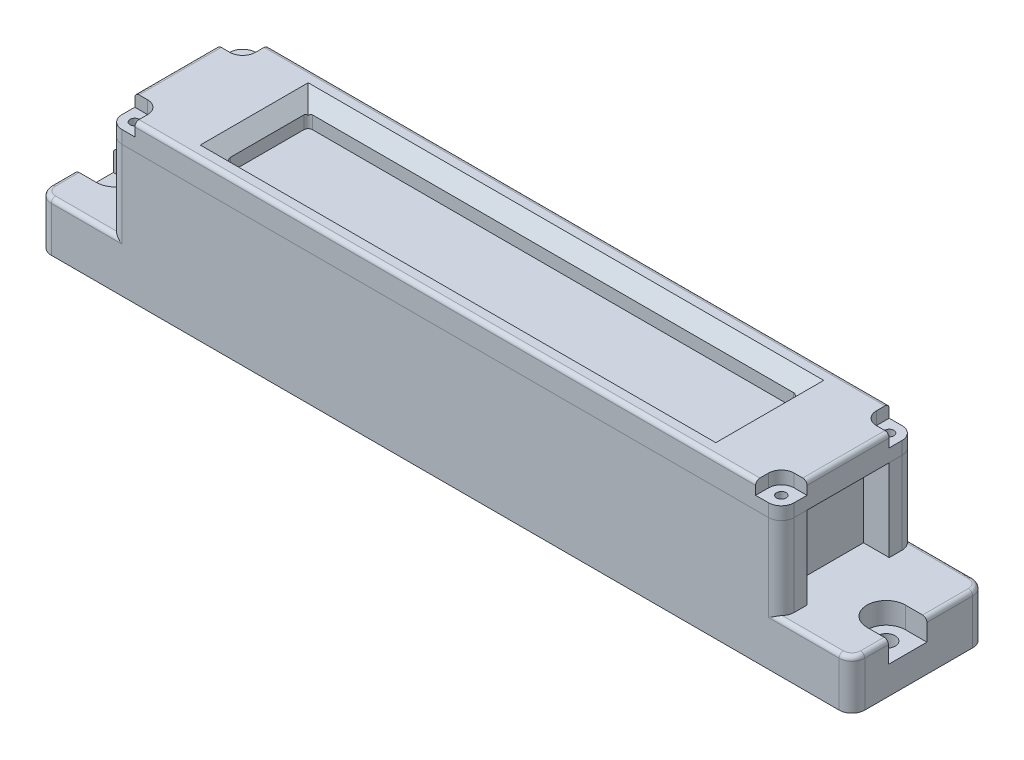
SolidWorks part; units mm, degrees
ref_plane "正面" through (0, 0, 0) normal (0, 0, 1) x (1, 0, 0)
ref_plane "平面" through (0, 0, 0) normal (0, 1, 0) x (1, 0, 0)
ref_plane "右側面" through (0, 0, 0) normal (1, 0, 0) x (0, 0, -1)
sketch "ｽｹｯﾁ1" plane through (0, 0, 0) normal (0, 1, 0) x (1, 0, 0)
  line L1 (-72.2, 11.6) -> (72.2, 11.6)
  line L2 (-72.2, 11.6) -> (-72.2, -11.6)
  line L3 (-72.2, -11.6) -> (72.2, -11.6)
  line L4 (72.2, 11.6) -> (72.2, -11.6)
  point P4 (-72.2, 0)
  point P6 (0, 11.6)
  dimension "D1" = 144.4
  dimension "D2" = 23.2
extrude "本体" add sketch "ｽｹｯﾁ1" along normal mid plane 23.2
sketch "ｽｹｯﾁ2" plane through (0, -11.6, 0) normal (0, -1, 0) x (1, 0, 0)
  line L0 (72.2, -11.6) -> (-72.2, -11.6) construction
  line L1 (-95, -15.6) -> (95, -15.6)
  line L2 (-95, -15.6) -> (-95, 15.6)
  line L3 (-95, 15.6) -> (95, 15.6)
  line L4 (95, -15.6) -> (95, 15.6)
  line L5 (-72.2, 0) -> (72.2, 0) construction
  line L6 (-72.2, -11.6) -> (-72.2, 11.6) construction
  line L7 (72.2, 11.6) -> (72.2, -11.6) construction
  line L8 (-85, -15.6) -> (-85, 15.6) construction
  line L9 (0, -15.6) -> (0, 15.6) construction
  line L18 (-72.6, 12) -> (-72.6, -12)
  line L19 (72.6, 12) -> (-72.6, 12)
  line L20 (72.6, -12) -> (72.6, 12)
  line L21 (-72.6, -12) -> (72.6, -12)
  line L22 (-72.6, 12) -> (-72.6, -12) construction
  line L23 (72.6, 12) -> (-72.6, 12) construction
  line L24 (72.6, -12) -> (72.6, 12) construction
  line L25 (-72.6, -12) -> (72.6, -12) construction
  circle A0 centre (-90, 2.6) radius 5 construction
  circle A1 centre (-90, 2.6) radius 2.1
  circle A2 centre (90, 2.6) radius 2.1
  point P12 (-95, 0)
  dimension "D3" = 10
  dimension "D4" = 4.2
  dimension "D1" = 4
  dimension "D2" = 12.8
  dimension "D6" = 13
  dimension "D7" = 180
  dimension "D5" = 0.4
extrude "ﾎﾞｽ - 押し出し2" add sketch "ｽｹｯﾁ2" along normal blind 6.5 separate body
sketch "ｽｹｯﾁ3" plane through (0, -11.6, 0) normal (0, 1, 0) x (1, 0, 0)
  line L0 (-95, -15.6) -> (-95, 15.6) construction
  line L1 (-90, 1.9) -> (-95, 1.9)
  line L3 (-90, -7.1) -> (-95, -7.1)
  line L4 (-95, 15.6) -> (-95, -15.6)
  line L5 (-95, -15.6) -> (95, -15.6)
  line L6 (95, -15.6) -> (95, 15.6)
  line L7 (95, 15.6) -> (-95, 15.6)
  line L8 (-95, 15.6) -> (-95, -15.6)
  line L9 (-95, -15.6) -> (95, -15.6)
  line L10 (95, -15.6) -> (95, 15.6)
  line L11 (95, 15.6) -> (-95, 15.6)
  line L19 (0, 15.6) -> (0, -15.6) construction
  line L20 (90, -7.1) -> (95, -7.1)
  line L21 (90, 1.9) -> (95, 1.9)
  line L23 (-72.5, 11.9) -> (-72.5, -11.9)
  line L24 (-72.5, -11.9) -> (72.5, -11.9)
  line L25 (72.5, -11.9) -> (72.5, 11.9)
  line L26 (72.5, 11.9) -> (-72.5, 11.9)
  line L27 (-72.5, 11.9) -> (-72.5, -11.9)
  line L28 (-72.5, -11.9) -> (72.5, -11.9)
  line L29 (72.5, -11.9) -> (72.5, 11.9)
  line L30 (72.5, 11.9) -> (-72.5, 11.9)
  arc A0 (-90, -7.1) -> (-90, 1.9) centre (-90, -2.6) ccw
  arc A1 (90, -7.1) -> (90, 1.9) centre (90, -2.6) cw
  line M12 (-95, 15.6) -> (-95, -15.6)
  line M13 (-95, -15.6) -> (95, -15.6)
  line M14 (95, -15.6) -> (95, 15.6)
  line M15 (95, 15.6) -> (-95, 15.6)
  dimension "D2" = 4.5
  dimension "D1" = 0
  dimension "D3" = 0.3
extrude "ﾎﾞｽ - 押し出し3" add sketch "ｽｹｯﾁ3" along normal blind 5 contours L19 L11 L1 A0 L3 L28 L27 L30 M12 M13 | L19 L30 L29 L28 L9 L20 A1 L21 M15 M14
sketch "ｽｹｯﾁ4" plane through (0, -6.6, 0) normal (0, 1, 0) x (1, 0, 0)
  line L0 (72.5, -11.9) -> (72.5, 11.9) construction
  line L1 (-72.5, -11.9) -> (72.5, -11.9) construction
  line L2 (72.5, 11.9) -> (-72.5, 11.9) construction
  line L3 (-72.5, 11.9) -> (-72.5, -11.9) construction
  line L4 (72.5, -11.9) -> (72.5, 11.9)
  line L5 (-72.5, -11.9) -> (72.5, -11.9)
  line L6 (72.5, 11.9) -> (-72.5, 11.9)
  line L7 (-72.5, 11.9) -> (-72.5, 9.6)
  line L8 (78.5, 15.6) -> (-78.5, 15.6)
  line L9 (-78.5, 15.6) -> (-78.5, 9.6)
  line L10 (-78.5, -15.6) -> (78.5, -15.6)
  line L11 (-78.5, -9.6) -> (-72.5, -9.6)
  line L12 (95, 15.6) -> (-95, 15.6) construction
  line L13 (-95, -15.6) -> (95, -15.6) construction
  line L14 (-78.5, 9.6) -> (-72.5, 9.6)
  line L15 (72.2, 11.6) -> (-72.2, 11.6) construction
  line L16 (-95, 0) -> (95, 0) construction
  line L17 (0, 15.6) -> (0, -15.6) construction
  line L18 (-78.5, -9.6) -> (-78.5, -15.6)
  line L19 (-72.5, -9.6) -> (-72.5, -11.9)
  line L20 (72.5, -9.6) -> (72.5, -11.9)
  line L21 (78.5, -9.6) -> (78.5, -15.6)
  line L22 (78.5, 9.6) -> (72.5, 9.6)
  line L23 (78.5, -9.6) -> (72.5, -9.6)
  line L24 (78.5, 15.6) -> (78.5, 9.6)
  line L25 (72.5, 11.9) -> (72.5, 9.6)
  line L27 (-95, -15.6) -> (-95, 15.6) construction
  circle A0 centre (-75.5, 12.6) radius 3 construction
  circle A1 centre (75.5, 12.6) radius 3 construction
  point P27 (0, 0)
  line M6 (-72.5, 11.9) -> (72.5, 11.9)
  line M7 (72.5, 11.9) -> (72.5, -11.9)
  line M8 (72.5, -11.9) -> (-72.5, -11.9)
  line M9 (-72.5, -11.9) -> (-72.5, 11.9)
  line M11 (95, 15.6) -> (-95, 15.6)
  line M17 (-95, -15.6) -> (95, -15.6)
  dimension "D1" = 6
  dimension "D2" = 2
extrude "ﾎﾞｽ - 押し出し4" add sketch "ｽｹｯﾁ4" along normal offset from surface (19.2 mm away) 1 contours L21 L23 L4 L11 L18 M8 M9 M17 | L24 L9 L14 L22 M11 M9 M6 M7 up to face at (0, 11.6, 0) offset beyond the face yes
sketch "ｽｹｯﾁ5" plane through (0, 12.6, 0) normal (0, 1, 0) x (1, 0, 0)
  line L0 (78.5, 15.6) -> (-78.5, 15.6) construction
  line L1 (-78.5, 9.6) -> (-72.5, 9.6) construction
  line L2 (-78.5, 15.6) -> (-78.5, 9.6) construction
  line L3 (0, 15.6) -> (0, -15.6) construction
  line L4 (-95, 15.6) -> (95, 15.6) construction
  line L5 (95, -15.6) -> (-95, -15.6) construction
  line L6 (-95, 0) -> (95, 0) construction
  line L7 (-95, -15.6) -> (-95, 15.6) construction
  circle A0 centre (-75.5, 12.6) radius 3 construction
  circle A1 centre (-75.5, 12.6) radius 1.1
  circle A2 centre (75.5, 12.6) radius 1.1
  circle A3 centre (75.5, -12.6) radius 1.1
  circle A4 centre (-75.5, -12.6) radius 1.1
  dimension "D1" = 2.2
extrude "ｶｯﾄ - 押し出し1" cut sketch "ｽｹｯﾁ5" against normal through all
sketch "ｽｹｯﾁ8" plane through (0, -11.6, 0) normal (0, 1, 0) x (1, 0, 0)
  line L0 (-72.5, 11.9) -> (-72.5, -11.9) construction
  line L1 (-57.5, 6.9) -> (57.5, 6.9)
  line L2 (-62.5, 1.9) -> (-62.5, -1.9)
  line L3 (-57.5, -6.9) -> (57.5, -6.9)
  line L4 (62.5, 1.9) -> (62.5, -1.9)
  line L5 (-72.5, -11.9) -> (72.5, -11.9) construction
  arc A0 (57.5, 6.9) -> (62.5, 1.9) centre (57.5, 1.9) cw
  arc A1 (57.5, -6.9) -> (62.5, -1.9) centre (57.5, -1.9) ccw
  arc A2 (-62.5, -1.9) -> (-57.5, -6.9) centre (-57.5, -1.9) ccw
  arc A3 (-57.5, 6.9) -> (-62.5, 1.9) centre (-57.5, 1.9) ccw
  point P4 (-62.5, 0)
  point P6 (0, 6.9)
  dimension "D3" = 5
  dimension "D1" = 10
  dimension "D2" = 5
extrude "ｶｯﾄ - 押し出し2" cut sketch "ｽｹｯﾁ8" against normal through all
sketch "ｽｹｯﾁ6" plane through (0, 12.6, 0) normal (0, 1, 0) x (1, 0, 0)
  line L0 (72.2, 11.6) -> (-72.2, 11.6) construction
  line L1 (-78.5, 15.6) -> (78.5, 15.6)
  line L2 (-78.5, 15.6) -> (-78.5, -15.6)
  line L3 (-78.5, -15.6) -> (78.5, -15.6)
  line L4 (78.5, 15.6) -> (78.5, -15.6)
  line L5 (-57.2, 9.6) -> (57.2, 9.6)
  line L6 (-57.2, 9.6) -> (-57.2, -9.6)
  line L7 (-57.2, -9.6) -> (57.2, -9.6)
  line L8 (57.2, 9.6) -> (57.2, -9.6)
  line L9 (-72.2, 11.6) -> (-72.2, -11.6) construction
  circle A0 centre (75.5, -12.6) radius 1.1 construction
  circle A1 centre (75.5, 12.6) radius 1.1 construction
  circle A2 centre (-75.5, -12.6) radius 1.1 construction
  circle A3 centre (-75.5, 12.6) radius 1.1 construction
  circle A4 centre (75.5, -12.6) radius 1.1
  circle A5 centre (75.5, 12.6) radius 1.1
  circle A6 centre (-75.5, -12.6) radius 1.1
  circle A7 centre (-75.5, 12.6) radius 1.1
  point P25 (-57.2, 0)
  point P27 (0, 9.6)
  dimension "D1" = 2
  dimension "D2" = 15
extrude "ﾎﾞｽ - 押し出し6" add sketch "ｽｹｯﾁ6" along normal blind 3 separate body
sketch "ｽｹｯﾁ7" plane through (0, 15.6, 0) normal (0, 1, 0) x (1, 0, 0)
  line L0 (-78.5, -15.6) -> (-72.5, -15.6)
  line L1 (-78.5, 15.6) -> (-72.5, 15.6)
  line L2 (-78.5, 15.6) -> (-78.5, 9.6)
  line L3 (-78.5, 9.6) -> (-72.5, 9.6)
  line L4 (-78.5, 15.6) -> (-78.5, -15.6)
  line L5 (-78.5, -15.6) -> (78.5, -15.6)
  line L6 (78.5, -15.6) -> (78.5, 15.6)
  line L7 (78.5, 15.6) -> (-78.5, 15.6)
  line L8 (-78.5, 15.6) -> (-78.5, -15.6)
  line L9 (-78.5, -15.6) -> (78.5, -15.6)
  line L10 (78.5, -15.6) -> (78.5, 15.6)
  line L11 (78.5, 15.6) -> (-78.5, 15.6)
  line L12 (-72.5, 15.6) -> (-72.5, 9.6)
  line L13 (-78.5, -9.6) -> (-78.5, -15.6)
  line L14 (-78.5, -9.6) -> (-72.5, -9.6)
  line L15 (-72.5, -9.6) -> (-72.5, -15.6)
  line L16 (72.5, 9.6) -> (78.5, 9.6)
  line L17 (72.5, 15.6) -> (72.5, 9.6)
  line L18 (72.5, 15.6) -> (78.5, 15.6)
  line L19 (78.5, 15.6) -> (78.5, 9.6)
  line L20 (72.5, -15.6) -> (78.5, -15.6)
  line L21 (72.5, -9.6) -> (72.5, -15.6)
  line L22 (72.5, -9.6) -> (78.5, -9.6)
  line L23 (78.5, -9.6) -> (78.5, -15.6)
  circle A0 centre (-75.5, 12.6) radius 3
  circle A1 centre (-75.5, -12.6) radius 3
  circle A2 centre (75.5, 12.6) radius 3
  circle A3 centre (75.5, -12.6) radius 3
  line M9 (-78.5, 15.6) -> (-78.5, -15.6)
  line M10 (-78.5, -15.6) -> (78.5, -15.6)
  line M15 (57.2, -9.6) -> (-57.2, -9.6)
  line M16 (-57.2, -9.6) -> (-57.2, 9.6)
  line M17 (-57.2, 9.6) -> (57.2, 9.6)
  line M18 (57.2, 9.6) -> (57.2, -9.6)
  dimension "D1" = 0
extrude "ﾎﾞｽ - 押し出し7" add sketch "ｽｹｯﾁ7" along normal blind 3 contours L21 L22 L10 L16 L17 L11 L12 L3 L14 L15 M9 M10 M18 M15 M16 M17 | A0 L3 L12 | A1 L15 L14 | A2 L17 L16 | A3 L22 L21
chamfer "面取り1" distance 3 angle 45 4 edges at (0, 18.6, 9.6) (0, 18.6, -9.6) (57.2, 18.6, 0) (-57.2, 18.6, 0)
fillet "ﾌｨﾚｯﾄ1" radius 3 8 edges at (95, -12.35, -15.6) (78.5, 3, -15.6) (95, -12.35, 15.6) (78.5, 3, 15.6) (-78.5, 3, -15.6) (-78.5, 3, 15.6) (-95, -12.35, -15.6) (-95, -12.35, 15.6)
fillet "ﾌｨﾚｯﾄ2" radius 3 4 edges at (-78.5, 14.1, -15.6) (-78.5, 14.1, 15.6) (78.5, 14.1, 15.6) (78.5, 14.1, -15.6)
fillet "ﾌｨﾚｯﾄ3" radius 1 8 edges at (-57.2, 14.1, 9.6) (57.2, 14.1, 9.6) (57.2, 14.1, -9.6) (-57.2, 14.1, -9.6) (78.5, 18.6, 0) (0, 18.6, 15.6) (0, 18.6, -15.6) (-78.5, 18.6, 0)
fillet "ﾌｨﾚｯﾄ4" radius 1 12 edges at (95, -6.6, 9.85) (83.75, -6.6, -15.6) (94.1213, -6.6, 14.7213) (94.1213, -6.6, -14.7213) (-83.75, -6.6, 15.6) (-95, -6.6, -7.25) (-94.1213, -6.6, 14.7213) (-94.1213, -6.6, -14.7213) (95, -6.6, -7.25) (-95, -6.6, 9.85) (83.75, -6.6, 15.6) (-83.75, -6.6, -15.6)
